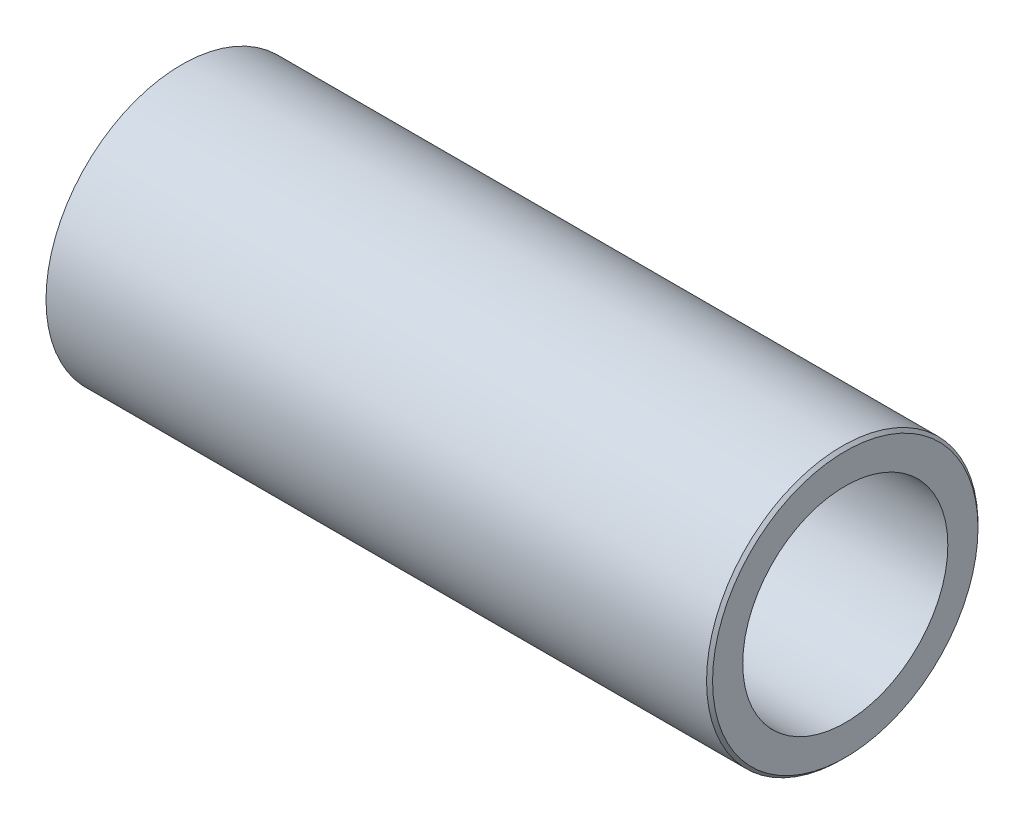
SolidWorks part; units mm, degrees
ref_plane "Front Plane" through (0, 0, 0) normal (0, 0, 1) x (1, 0, 0)
ref_plane "Top Plane" through (0, 0, 0) normal (0, 1, 0) x (1, 0, 0)
ref_plane "Right Plane" through (0, 0, 0) normal (1, 0, 0) x (0, 0, -1)
sketch "Sketch1" plane through (0, 0, 0) normal (0, 0, 1) x (1, 0, 0)
  line L0 (-14.4, 0) -> (14.4, 0) construction
  line L1 (-64, 9) -> (-64, -9) construction
  line L2 (-64, 9) -> (-60, 9)
  line L3 (-60, 9) -> (-60, 12)
  line L4 (-60, 12) -> (0, 12)
  line L5 (0, 12) -> (0, 17)
  line L6 (0, 17) -> (46, 17)
  line L7 (46, 17) -> (46, 22.5)
  line L8 (46, 22.5) -> (-64, 22.5)
  line L9 (-64, 22.5) -> (-64, 9)
  point P4 (0, 0)
  point P8 (-64, 0)
  dimension "D1" = 18
  dimension "D2" = 34
  dimension "D3" = 24
  dimension "D4" = 45
  dimension "D5" = 110
  dimension "D6" = 46
  dimension "D7" = 60
revolve "Revolve1" add sketch "Sketch1" angle 360 about L0
chamfer "Chamfer1" distance 0.5 angle 45 1 edges at (46, 0, 22.5)
